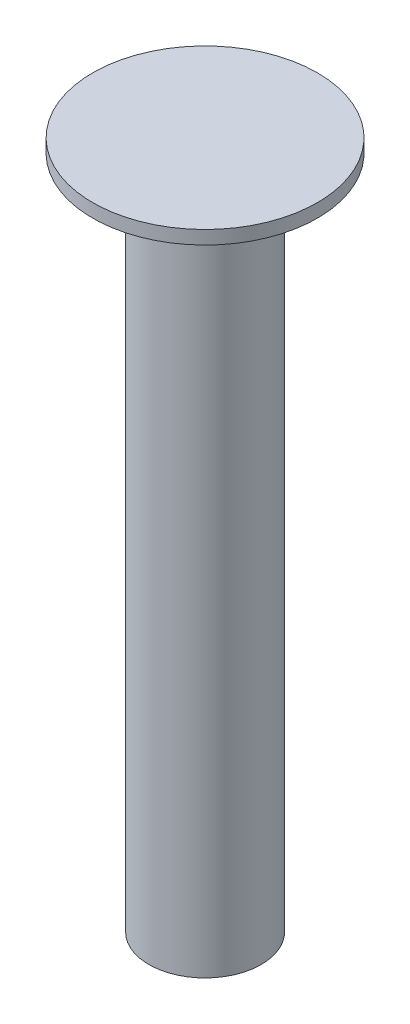
SolidWorks part; units mm, degrees
material "Plain Carbon Steel"
ref_plane "Front Plane" through (0, 0, 0) normal (0, 0, 1) x (1, 0, 0)
ref_plane "Top Plane" through (0, 0, 0) normal (0, 1, 0) x (1, 0, 0)
ref_plane "Right Plane" through (0, 0, 0) normal (1, 0, 0) x (0, 0, -1)
sketch "Sketch1" plane through (0, 0, 0) normal (0, 1, 0) x (1, 0, 0)
  circle A0 centre (0, 0) radius 6.35
  dimension "D1" = 12.7
extrude "Boss-Extrude1" add sketch "Sketch1" along normal blind 76.2 contours A0
sketch "Sketch2" plane through (0, 76.2, 0) normal (0, 1, 0) x (1, 0, 0)
  circle A0 centre (0, 0) radius 12.7
  dimension "D1" = 25.4
extrude "Boss-Extrude2" add sketch "Sketch2" along normal blind 1.524
